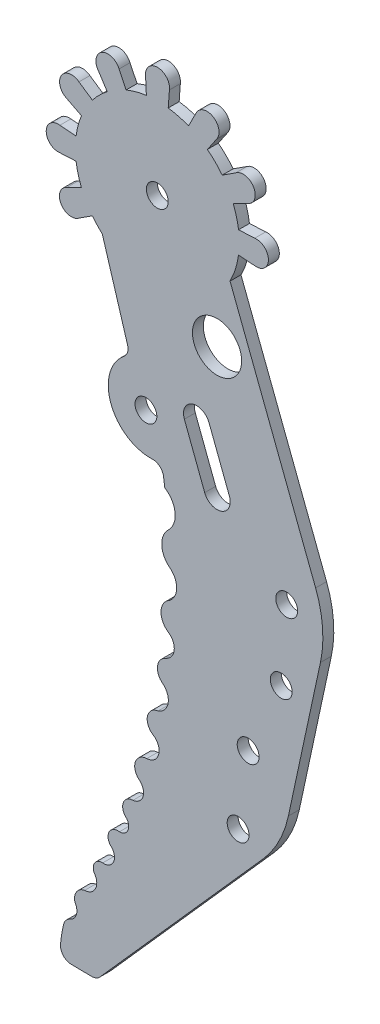
SolidWorks part; units mm, degrees
ref_plane "Front Plane" through (0, 0, 0) normal (0, 0, 1) x (1, 0, 0)
ref_plane "Top Plane" through (0, 0, 0) normal (0, 1, 0) x (1, 0, 0)
ref_plane "Right Plane" through (0, 0, 0) normal (1, 0, 0) x (0, 0, -1)
sketch "Sketch1" plane through (0, 0, 0) normal (0, 0, 1) x (1, 0, 0)
  line L0 (10.1632, 0) -> (2.5, 0) construction
  line L1 (2.7301, 1) -> (1.25, 1.1081)
  line L2 (2.7301, -1) -> (1.25, -1.0732)
  line L3 (1, 0) -> (0, 0) construction
  line L4 (3.226, 2.8505) -> (1.9075, 3.5272)
  line L5 (4.226, 4.5825) -> (2.9982, 5.4162)
  line L6 (5.5806, 5.9372) -> (4.7772, 7.1824)
  line L7 (7.3127, 6.9372) -> (6.6662, 8.2731)
  line L8 (9.1632, 7.433) -> (9.09, 8.9132)
  line L9 (11.1632, 7.433) -> (11.2713, 8.9132)
  line L10 (13.0137, 6.9372) -> (13.6904, 8.2556)
  line L11 (14.7457, 5.9372) -> (15.5794, 7.165)
  line L12 (16.1004, 4.5825) -> (17.3456, 5.386)
  line L13 (17.1004, 2.8505) -> (18.4363, 3.497)
  line L14 (17.5962, 1) -> (19.0764, 1.0732)
  line L15 (17.5962, -1) -> (19.0764, -1.1081)
  line L16 (5.1316, -5.5618) -> (7.4417, -13.2)
  line L17 (16.8182, -3.4583) -> (24.6469, -23.8519)
  line L18 (25.0875, -29.5388) -> (22.1552, -43.1693)
  line L19 (19.858, -47.7041) -> (4.914, -64.542)
  line L20 (4.1518, -64.8781) -> (2.2863, -64.8515)
  line L21 (10.1806, 10.1633) -> (-3.4833, 10.1633) construction
  line L22 (2.5, 0) -> (0, 0) construction
  line L23 (0, 0) -> (0, -102.3289) construction
  line L24 (4.226, -4.5825) -> (2.9807, -5.386)
  line L25 (3.226, -2.8505) -> (1.8901, -3.497)
  line L26 (9.1632, -7.433) -> (9.0551, -8.9132) [skipped]
  line L27 (11.1632, -7.433) -> (11.2364, -8.9132) [skipped]
  line L28 (14.7457, -5.9372) -> (15.5492, -7.1824) [skipped]
  line L29 (13.0137, -6.9372) -> (13.6601, -8.2731) [skipped]
  line L30 (16.1004, -4.5825) -> (17.3282, -5.4162) [skipped]
  line L31 (17.1004, -2.8505) -> (18.4188, -3.5272) [skipped]
  line L32 (7.3127, -6.9372) -> (6.636, -8.2556) [skipped]
  line L33 (5.5806, -5.9372) -> (4.747, -7.165) [skipped]
  line L34 (15.628, -20.9466) -> (13.7664, -16.0577) construction
  line L35 (14.5003, -21.376) -> (12.6387, -16.4871)
  line L36 (16.7556, -20.5172) -> (14.8941, -15.6283)
  line L37 (22, -26.4997) -> (42.7977, -26.4997) construction
  line L38 (17.5548, -46.4997) -> (44.5231, -46.4997) construction
  line L39 (22, -26.4997) -> (21.5, -33.1664) construction
  arc A1 (3.226, 2.8505) -> (2.7301, 1) centre (10.1632, 0) ccw
  arc A3 (1.25, -1.0732) -> (1.25, 1.1081) centre (1.1007, 0.0174) cw
  arc A4 (1.9075, 3.5272) -> (2.9982, 5.4162) centre (2.3235, 4.5464) cw
  arc A5 (4.7772, 7.1824) -> (6.6662, 8.2731) centre (5.647, 7.8571) cw
  arc A6 (9.09, 8.9132) -> (11.2713, 8.9132) centre (10.1806, 9.0625) cw
  arc A7 (13.6904, 8.2556) -> (15.5794, 7.165) centre (14.7095, 7.8396) cw
  arc A8 (17.3456, 5.386) -> (18.4363, 3.497) centre (18.0203, 4.5161) cw
  arc A9 (19.0764, 1.0732) -> (19.0764, -1.1081) centre (19.2257, -0.0174) cw
  arc A10 (5.5806, 5.9372) -> (4.226, 4.5825) centre (10.1632, 0) ccw
  arc A11 (9.1632, 7.433) -> (7.3127, 6.9372) centre (10.1632, 0) ccw
  arc A12 (13.0137, 6.9372) -> (11.1632, 7.433) centre (10.1632, 0) ccw
  arc A13 (7.1115, -14.2685) -> (9.6978, -21.1131) centre (9.5249, -17.2675) ccw
  arc A14 (2.9807, -5.386) -> (1.8901, -3.497) centre (2.3061, -4.5161) cw
  arc A15 (11.2364, -8.9132) -> (9.0551, -8.9132) centre (10.1457, -9.0625) cw [skipped]
  arc A16 (15.5492, -7.1824) -> (13.6601, -8.2731) centre (14.6793, -7.8571) cw [skipped]
  arc A17 (18.4188, -3.5272) -> (17.3282, -5.4162) centre (18.0028, -4.5464) cw [skipped]
  arc A18 (2.7301, -1) -> (3.226, -2.8505) centre (10.1632, 0) ccw
  arc A19 (4.226, -4.5825) -> (5.1316, -5.5618) centre (10.1632, 0) ccw
  arc A20 (16.1004, 4.5825) -> (14.7457, 5.9372) centre (10.1632, 0) ccw
  arc A21 (17.5962, 1) -> (17.1004, 2.8505) centre (10.1632, 0) ccw
  arc A22 (6.636, -8.2556) -> (4.747, -7.165) centre (5.6168, -7.8396) cw [skipped]
  arc A23 (10.7326, -21.97) -> (10.8477, -22.8183) centre (-44.6411, -29.9177) cw
  arc A24 (1.5967, -62.0191) -> (1.3051, -63.7569) centre (13.5916, -64.9251) ccw
  arc A25 (4.914, -64.542) -> (4.1518, -64.8781) centre (4.1661, -63.8782) cw
  arc A26 (2.2863, -64.8515) -> (1.3051, -63.7569) centre (2.3006, -63.8516) cw
  arc A27 (22.1552, -43.1693) -> (19.858, -47.7041) centre (12.3789, -41.0662) cw
  arc A28 (24.6469, -23.8519) -> (25.0875, -29.5388) centre (15.3111, -27.4357) cw
  arc A29 (16.8182, -3.4583) -> (17.5962, -1) centre (10.1632, 0) ccw
  circle A30 centre (10.1632, 0) radius 1
  circle A31 centre (15.628, -9.2603) radius 2.25
  circle A32 centre (9.1218, -17.5263) radius 0.9981
  arc A33 (14.5003, -21.376) -> (16.7556, -20.5172) centre (15.628, -20.9466) ccw
  arc A34 (14.8941, -15.6283) -> (12.6387, -16.4871) centre (13.7664, -16.0577) ccw
  circle A35 centre (22, -26.4997) radius 1
  circle A36 centre (21.5, -33.1664) radius 1
  circle A37 centre (18.4742, -39.833) radius 1
  circle A38 centre (17.5548, -46.4997) radius 1
  arc A39 (3.5195, -58.3776) -> (4.478, -56.6894) centre (3.4947, -57.2474) ccw
  arc A40 (4.478, -56.6894) -> (5.1728, -55.3731) centre (5.1184, -56.1859) cw
  arc A41 (5.1728, -55.3731) -> (5.9791, -53.7296) centre (5.2695, -54.401) ccw
  arc A42 (5.9791, -53.7296) -> (6.6933, -52.1481) centre (6.5575, -53.0388) cw
  arc A43 (6.6933, -52.1481) -> (7.2971, -50.6981) centre (6.7052, -51.3023) ccw
  arc A44 (7.2971, -50.6981) -> (7.932, -49.0351) centre (7.9512, -49.9951) cw
  arc A45 (7.932, -49.0351) -> (8.5712, -47.1764) centre (7.8216, -47.9579) ccw
  arc A46 (8.5712, -47.1764) -> (9.2023, -45.0931) centre (9.247, -46.2439) cw
  arc A47 (9.2023, -45.0931) -> (9.7684, -42.9183) centre (9.1568, -43.9202) ccw
  arc A48 (9.7684, -42.9183) -> (10.2303, -40.8052) centre (10.39, -41.9471) cw
  arc A49 (10.2303, -40.8052) -> (10.6508, -38.4154) centre (9.7964, -39.497) ccw
  arc A50 (10.6508, -38.4154) -> (10.9372, -36.2787) centre (11.4277, -37.432) cw
  arc A51 (10.9372, -36.2787) -> (11.1453, -34.0756) centre (10.4704, -35.1232) ccw
  arc A52 (11.1453, -34.0756) -> (11.277, -31.5211) centre (12.0035, -32.8392) cw
  arc A53 (11.277, -31.5211) -> (11.2908, -28.902) centre (10.2837, -30.2063) ccw
  arc A54 (11.2908, -28.902) -> (11.1632, -26.0077) centre (12.4931, -27.399) cw
  arc A55 (11.1632, -26.0077) -> (10.8477, -22.8183) centre (9.7776, -24.5344) ccw
  arc A57 (9.6978, -21.1131) -> (10.7326, -21.97) centre (9.7427, -22.112) cw
  arc A58 (7.4417, -13.2) -> (7.1115, -14.2685) centre (6.4845, -13.4895) cw
  arc A59 (3.5195, -58.3776) -> (2.639, -59.7833) centre (3.7042, -59.4719) ccw
  arc A60 (2.639, -59.7833) -> (2.1678, -61.3383) centre (1.7398, -60.3597) cw
  arc A61 (2.1678, -61.3383) -> (1.5967, -62.0191) centre (2.5686, -62.2545) ccw
  point P59 (1.25, -64.8367)
  point P68 (10.1632, 0)
  point P105 (14.6972, -18.5021)
  point P119 (11.1632, -26.0077)
  point P122 (11.2908, -28.902)
  point P123 (11.277, -31.5211)
  point P124 (11.1453, -34.0756)
  point P125 (10.9372, -36.2787)
  point P126 (10.6508, -38.4154)
  point P127 (10.8477, -22.8183)
  point P128 (10.2303, -40.8052)
  point P129 (9.7684, -42.9183)
  point P130 (9.2023, -45.0931)
  point P131 (8.5712, -47.1764)
  point P132 (7.932, -49.0351)
  point P133 (7.2971, -50.6981)
  point P134 (6.6933, -52.1481)
  point P135 (5.9791, -53.7296)
  point P136 (5.1728, -55.3731)
  point P137 (4.478, -56.6894)
  point P138 (3.5195, -58.3776)
  dimension "D1" = 12
  dimension "D2" = 15
  dimension "D5" = 75
  dimension "D6" = 1
  dimension "D7" = 10
  dimension "D8" = 2
  dimension "D9" = 4.5
  dimension "D10" = 1.9961
  dimension "D12" = 2
  dimension "D15" = 1
  dimension "D16" = 1
  dimension "D3" = 1
  dimension "D4" = 2.5
  dimension "D11" = 20
  dimension "D13" = 6.6667
  dimension "D14" = 6.6667
  dimension "D17" = 26.4997
  dimension "D18" = 22
  dimension "D19" = 17.5548
  dimension "D20" = 6.6854
extrude "Boss-Extrude1" add sketch "Sketch1" along normal blind 1
